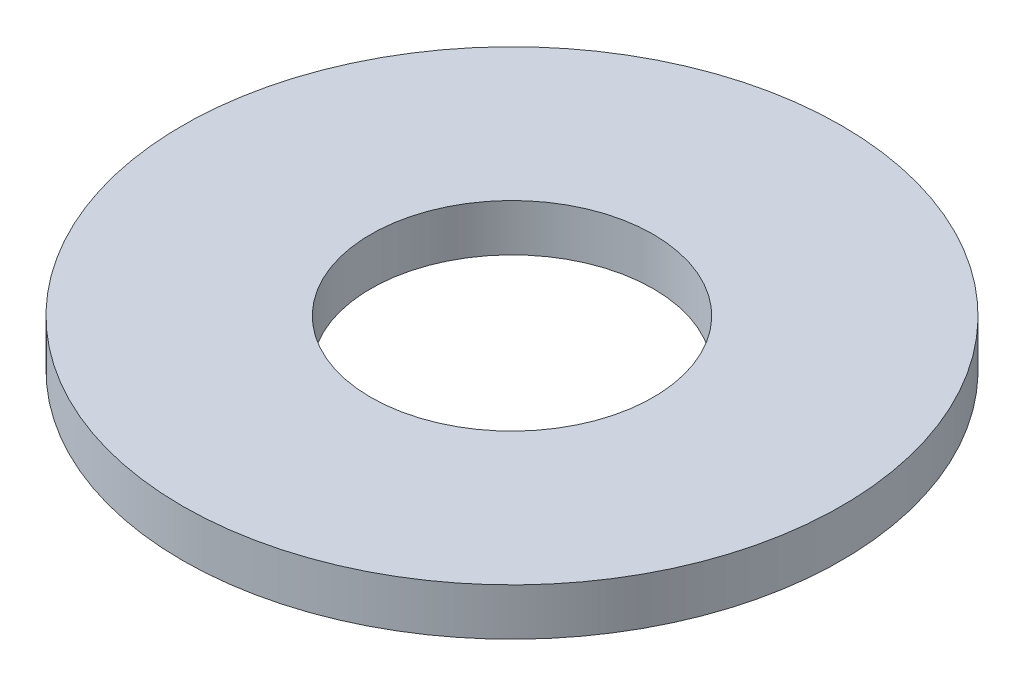
SolidWorks part; units mm, degrees
ref_plane "Front Plane" through (0, 0, 0) normal (0, 0, 1) x (1, 0, 0)
ref_plane "Top Plane" through (0, 0, 0) normal (0, 1, 0) x (1, 0, 0)
ref_plane "Right Plane" through (0, 0, 0) normal (1, 0, 0) x (0, 0, -1)
sketch "Sketch1" plane through (0, 0, 0) normal (0, 1, 0) x (1, 0, 0)
  circle A0 centre (0, 0) radius 35
  circle A1 centre (0, 0) radius 15
  dimension "D1" = 70
  dimension "D2" = 30
extrude "Boss-Extrude1" add sketch "Sketch1" along normal blind 5
